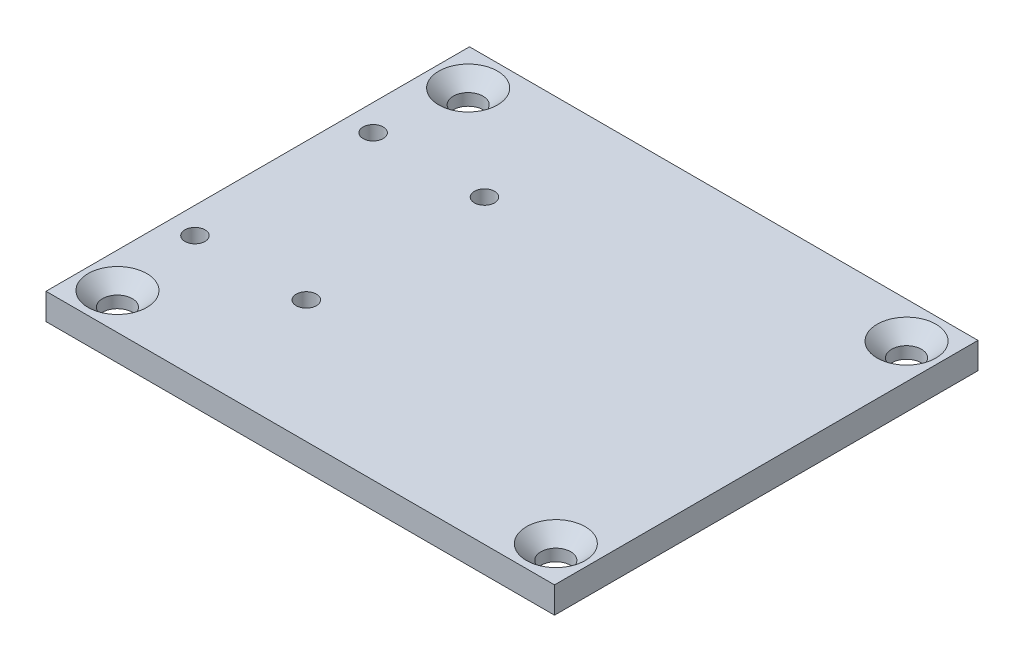
SolidWorks part; units mm, degrees
ref_plane "Front Plane" through (0, 0, 0) normal (0, 0, 1) x (1, 0, 0)
ref_plane "Top Plane" through (0, 0, 0) normal (0, 1, 0) x (1, 0, 0)
ref_plane "Right Plane" through (0, 0, 0) normal (1, 0, 0) x (0, 0, -1)
sketch "Sketch1" plane through (0, 0, 0) normal (0, 1, 0) x (1, 0, 0)
  line L1 (-29, -24.15) -> (29, -24.15)
  line L2 (-29, -24.15) -> (-29, 24.15)
  line L3 (-29, 24.15) -> (29, 24.15)
  line L4 (29, -24.15) -> (29, 24.15)
  line L5 (-29, -24.15) -> (29, 24.15) construction
  line L6 (-29, 24.15) -> (29, -24.15) construction
  point P0 (0, 0)
  point P9 (0, 0)
  dimension "D1" = 48.3
  dimension "D2" = 58
extrude "Boss-Extrude1" add sketch "Sketch1" along normal blind 3
sketch "Sketch2" plane through (0, 3, 0) normal (0, 1, 0) x (1, 0, 0)
  line L1 (-25, -20) -> (25, -20) construction
  line L2 (-25, -20) -> (-25, 20) construction
  line L3 (-25, 20) -> (25, 20) construction
  line L4 (25, -20) -> (25, 20) construction
  line L5 (-25, -20) -> (25, 20) construction
  line L6 (-25, 20) -> (25, -20) construction
  point P0 (0, 0)
  point P1 (25, 20)
  point P2 (-25, -20)
  point P3 (-25, 20)
  point P4 (25, -20)
  dimension "D1" = 40
  dimension "D2" = 50
hole_wizard "CSK for M3 Flat Head Machine Screw1" positions "Sketch2" profile "Sketch3" countersink size "M3" standard "ANSI Metric"
sketch "Sketch3" plane through (25, 3, 20) normal (1, 0, 0) x (0, 0, 1)
  line L0 (0, 0) -> (0, 3)
  line L1 (0, 3) -> (1.7, 3)
  line L2 (1.7, 3) -> (1.7, 1.65)
  line L3 (1.7, 1.65) -> (3.35, 0)
  line L5 (3.35, 0) -> (0, 0)
  line L6 (-1.7, 1.65) -> (-3.35, 0) construction
  line L11 (0, -6.35) -> (0, 107.95) construction
  dimension "Thru Hole Dia." = 3.4
  dimension "Thru Hole Depth" = 3
  dimension "Near C'Sink Dia." = 6.7
  dimension "Near C'Sink Angle" = 90
sketch "Sketch4" plane through (0, 3, 0) normal (0, 1, 0) x (1, 0, 0)
  line L0 (0, -15) -> (0, 15) construction
  point P4 (0, 0)
  point P6 (0, 15)
  point P7 (0, -15)
  dimension "D1" = 30
hole_wizard "M4x0.7 Tapped Hole1" [suppressed] positions "Sketch4" profile "Sketch5" tap size "M4x0.7" standard "ANSI Metric"
sketch "Sketch5" plane through (0, 3, 15) normal (1, 0, 0) x (0, 0, 1)
  line L0 (0, 0) -> (0, 3)
  line L1 (0, 3) -> (1.65, 3)
  line L2 (1.65, 3) -> (1.65, 0)
  line L5 (1.65, 0) -> (0, 0)
  line L11 (0, -6.35) -> (0, 107.95) construction
  dimension "Thru Tap Drill Dia." = 3.3
  dimension "Thru Tap Drill Depth" = 3
cosmetic thread "Hole Thread1" [suppressed] parameters "D2"=4
cosmetic thread "Hole Thread2" [suppressed] parameters "D2"=4
sketch "Sketch6" plane through (0, 3, 0) normal (0, 1, 0) x (1, 0, 0)
  circle A0 centre (-26, 10.16) radius 1.15
  circle A1 centre (-13.3, 10.16) radius 1.15
  circle A2 centre (-13.3, -10.16) radius 1.15
  circle A3 centre (-26, -10.16) radius 1.15
  dimension "D1" = 2.3
  dimension "D5" = 10.16
  dimension "D4" = 26
  dimension "D2" = 2
  dimension "D3" = 2
extrude "Cut-Extrude1" cut sketch "Sketch6" against normal blind 10
